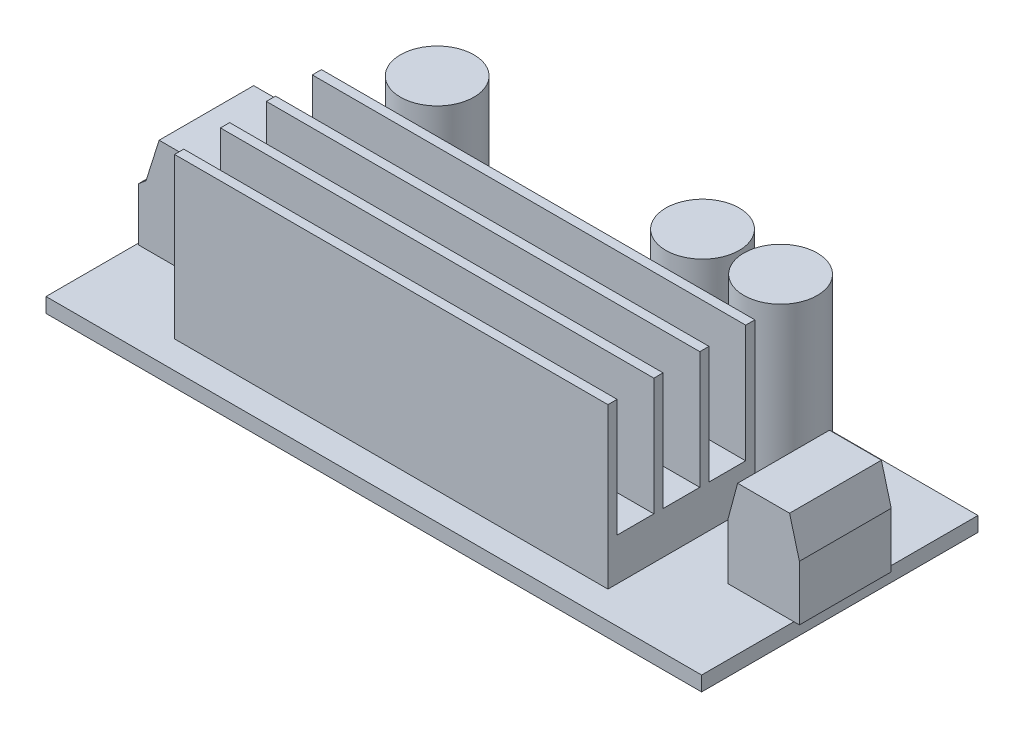
SolidWorks part; units mm, degrees
ref_plane "Front Plane" through (0, 0, 0) normal (0, 0, 1) x (1, 0, 0)
ref_plane "Top Plane" through (0, 0, 0) normal (0, 1, 0) x (1, 0, 0)
ref_plane "Right Plane" through (0, 0, 0) normal (1, 0, 0) x (0, 0, -1)
sketch "Sketch1" plane through (0, 0, 0) normal (0, 1, 0) x (1, 0, 0)
  line L1 (35.7, 15.05) -> (-35.7, 15.05)
  line L2 (35.7, 15.05) -> (35.7, -15.05)
  line L3 (35.7, -15.05) -> (-35.7, -15.05)
  line L4 (-35.7, 15.05) -> (-35.7, -15.05)
  line L5 (35.7, 15.05) -> (-35.7, -15.05) construction
  line L6 (35.7, -15.05) -> (-35.7, 15.05) construction
  point P0 (0, 0)
  dimension "D1" = 71.4
  dimension "D2" = 30.1
extrude "Boss-Extrude1" add sketch "Sketch1" along normal blind 1.6
sketch "Sketch4" plane through (0, 1.6, 0) normal (0, 1, 0) x (1, 0, 0)
  line L0 (-35.7, -15.05) -> (35.7, -15.05) construction
  line L1 (-24.7, 3.95) -> (22.5, 3.95)
  line L2 (-24.7, 3.95) -> (-24.7, -12.05)
  line L3 (-24.7, -12.05) -> (22.5, -12.05)
  line L4 (22.5, 3.95) -> (22.5, -12.05)
  line L5 (-35.7, 15.05) -> (-35.7, -15.05) construction
  dimension "D1" = 47.2
  dimension "D2" = 16
  dimension "D3" = 3
  dimension "D4" = 11
extrude "Boss-Extrude2" add sketch "Sketch4" along normal blind 17.4
sketch "Sketch5" plane through (0, 1.6, 0) normal (0, 1, 0) x (1, 0, 0)
  line L0 (-35.7, 0) -> (-35.5, 0) construction
  line L1 (-35.5, 5.15) -> (-25.2, 5.15)
  line L2 (-35.5, 5.15) -> (-35.5, -5.15)
  line L3 (-35.5, -5.15) -> (-25.2, -5.15)
  line L4 (-25.2, 5.15) -> (-25.2, -5.15)
  line L5 (-35.7, 15.05) -> (-35.7, -15.05) construction
  dimension "D1" = 10.3
  dimension "D2" = 10.3
  dimension "D3" = 0.2
extrude "Boss-Extrude3" add sketch "Sketch5" along normal blind 11
sketch "Sketch6" plane through (0, 1.6, 0) normal (0, 1, 0) x (1, 0, 0)
  line L0 (36.3, 0) -> (35.7, 0) construction
  line L1 (36.3, 5) -> (28.5, 5)
  line L2 (36.3, 5) -> (36.3, -5)
  line L3 (36.3, -5) -> (28.5, -5)
  line L4 (28.5, 5) -> (28.5, -5)
  line L5 (35.7, -15.05) -> (35.7, 15.05) construction
  dimension "D1" = 10
  dimension "D2" = 7.8
  dimension "D3" = 0.6
extrude "Boss-Extrude4" add sketch "Sketch6" along normal blind 10
sketch "Sketch7" plane through (0, 1.6, 0) normal (0, 1, 0) x (1, 0, 0)
  line L0 (35.7, 15.05) -> (-35.7, 15.05) construction
  line L5 (-35.7, 15.05) -> (-35.7, -15.05) construction
  line L6 (35.7, -15.05) -> (35.7, -5) construction
  circle A0 centre (18.7, 10.55) radius 4
  circle A1 centre (10.2, 10.55) radius 4
  circle A2 centre (-18.7, 10.55) radius 4
  point P8 (0, 0)
  dimension "D1" = 8
  dimension "D2" = 8.5
  dimension "D3" = 4.5
  dimension "D4" = 17
  dimension "D5" = 17
extrude "Boss-Extrude5" add sketch "Sketch7" along normal blind 16.5
sketch "Sketch8" plane through (-24.7, 0, 0) normal (-1, 0, 0) x (0, 0, 1)
  line L0 (-3.95, 19) -> (12.05, 19) construction
  line L1 (-2.95, 19) -> (1.05, 19)
  line L2 (-2.95, 19) -> (-2.95, 6.2)
  line L3 (-2.95, 6.2) -> (1.05, 6.2)
  line L4 (1.05, 19) -> (1.05, 6.2)
  line L5 (2.05, 19) -> (2.05, 6.2)
  line L6 (2.05, 19) -> (6.05, 19)
  line L7 (6.05, 19) -> (6.05, 6.2)
  line L8 (2.05, 6.2) -> (6.05, 6.2)
  line L9 (7.05, 19) -> (7.05, 6.2)
  line L10 (7.05, 19) -> (11.05, 19)
  line L11 (11.05, 19) -> (11.05, 6.2)
  line L12 (7.05, 6.2) -> (11.05, 6.2)
  line L13 (-3.95, 19) -> (-3.95, 1.6) construction
  line L14 (12.05, 19) -> (12.05, 1.6) construction
  dimension "D1" = 3
  dimension "D2" = 1
  dimension "D3" = 1
  dimension "D4" = 1
  dimension "D5" = 12.8
extrude "Cut-Extrude1" cut sketch "Sketch8" against normal up to surface (47.2 mm away) up to face at (22.5, 10.3, 4.05)
sketch "Sketch9" plane through (0, 0, 5.15) normal (0, 0, 1) x (1, 0, 0)
  line L0 (-35.5, 7.4018) -> (-34.71, 8.0599)
  line L1 (-35.5, 12.6) -> (-35.5, 1.6) construction
  line L2 (-34.71, 8.0599) -> (-33.2802, 12.6)
  line L3 (-35.5, 12.6) -> (-25.2, 12.6) construction
  line L4 (-25.2, 6.115) -> (-26.8364, 12.6)
  line L8 (-35.5, 1.6) -> (-25.2, 1.6)
  line L9 (-25.2, 1.6) -> (-25.2, 12.6)
  line L10 (-25.2, 12.6) -> (-35.5, 12.6)
  line L11 (-35.5, 12.6) -> (-35.5, 1.6)
  line L12 (-35.5, 1.6) -> (-25.2, 1.6)
  line L13 (-25.2, 1.6) -> (-25.2, 12.6)
  line L14 (-25.2, 12.6) -> (-35.5, 12.6)
  line L15 (-35.5, 12.6) -> (-35.5, 1.6)
  point P9 (-26.8364, 12.6)
  line M6 (-25.2, 1.6) -> (-25.2, 12.6)
  line M7 (-25.2, 12.6) -> (-35.5, 12.6)
  line M8 (-35.5, 12.6) -> (-35.5, 1.6)
  dimension "D1" = 0
extrude "Cut-Extrude2" cut sketch "Sketch9" against normal up to surface (10.3 mm away) contours L0 L2 M7 M8 | L4 M6 M7 up to face at (-30.35, 7.1, -5.15)
chamfer "Chamfer1" distance 4 angle 15 2 edges at (28.5, 11.6, 0) (36.3, 11.6, 0)
